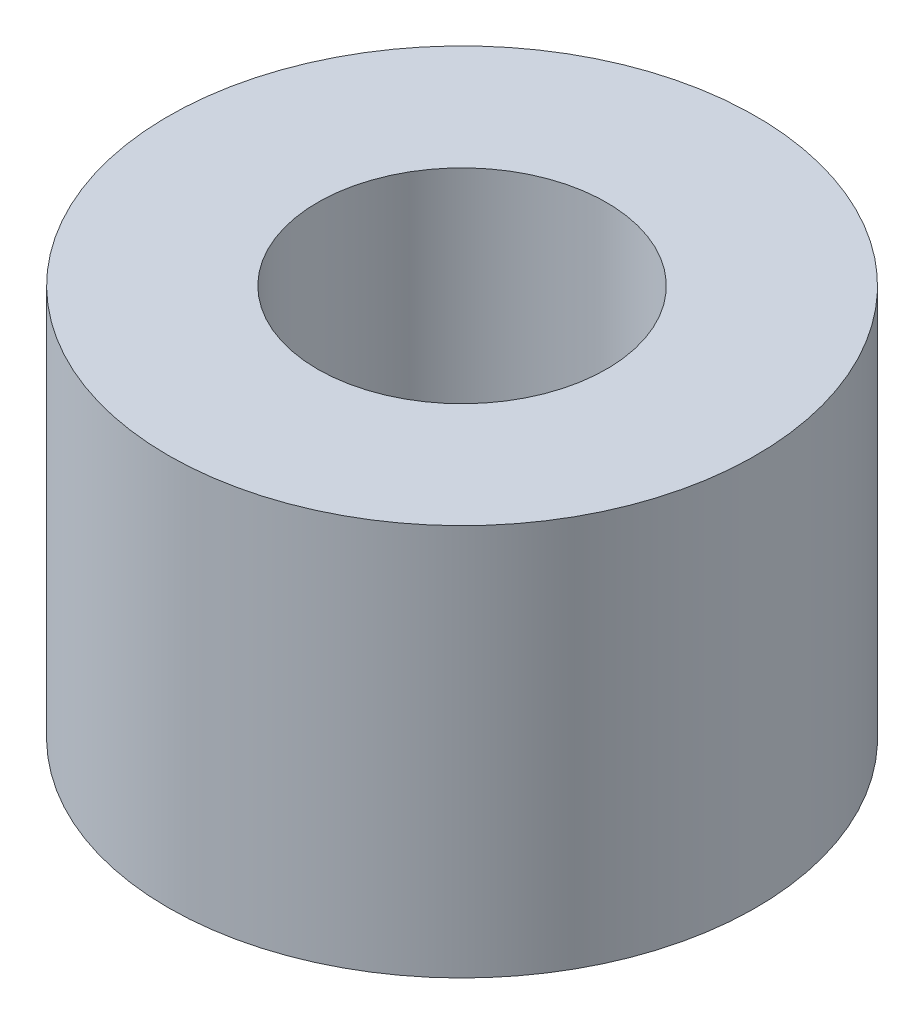
SolidWorks part; units mm, degrees
ref_plane "Front Plane" through (0, 0, 0) normal (0, 0, 1) x (1, 0, 0)
ref_plane "Top Plane" through (0, 0, 0) normal (0, 1, 0) x (1, 0, 0)
ref_plane "Right Plane" through (0, 0, 0) normal (1, 0, 0) x (0, 0, -1)
sketch "Sketch1" plane through (0, 0, 0) normal (0, 1, 0) x (1, 0, 0)
  circle A0 centre (0, 0) radius 3
  dimension "D1" = 6
extrude "Boss-Extrude1" add sketch "Sketch1" along normal blind 4 contours A0
sketch "Sketch2" plane through (0, 4, 0) normal (0, 1, 0) x (1, 0, 0)
  circle A0 centre (0, 0) radius 1.475
  dimension "D1" = 2.95
extrude "Cut-Extrude1" cut sketch "Sketch2" against normal through all
